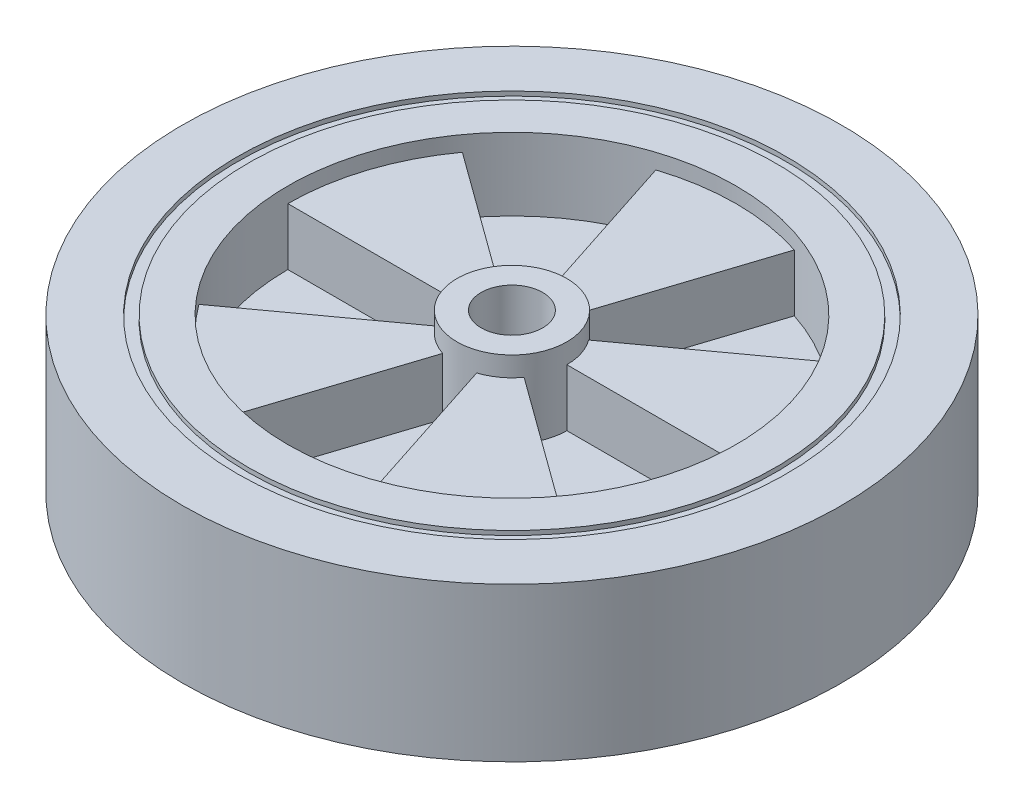
SolidWorks part; units mm, degrees
ref_plane "Front Plane" through (0, 0, 0) normal (0, 0, 1) x (1, 0, 0)
ref_plane "Top Plane" through (0, 0, 0) normal (0, 1, 0) x (1, 0, 0)
ref_plane "Right Plane" through (0, 0, 0) normal (1, 0, 0) x (0, 0, -1)
sketch "Sketch1" plane through (0, 0, 0) normal (0, 1, 0) x (1, 0, 0)
  circle A0 centre (0, 0) radius 7
  circle A1 centre (0, 0) radius 75
  circle A2 centre (0, 0) radius 51
  dimension "D1" = 14
  dimension "D2" = 150
  dimension "D3" = 102
extrude "Boss-Extrude1" add sketch "Sketch1" along normal mid plane 35 contours A1 A2
sketch "Sketch2" plane through (0, 0, 0) normal (0, 1, 0) x (1, 0, 0)
  circle A0 centre (0, 0) radius 12.5
  circle A1 centre (0, 0) radius 7
  dimension "D1" = 25
  dimension "D2" = 14
extrude "Boss-Extrude2" add sketch "Sketch2" along normal mid plane 37 separate body
sketch "Sketch3" plane through (0, 0, 0) normal (0, 1, 0) x (1, 0, 0)
  line L0 (0, 12.5) -> (0, 51) construction
  line L1 (3.8627, 11.8882) -> (15.7599, 48.5039)
  line L2 (-3.8627, 11.8882) -> (-15.7599, 48.5039)
  line L3 (12.5, 0) -> (51, 0)
  line L4 (10.1127, 7.3473) -> (41.2599, 29.977)
  line L5 (3.8627, -11.8882) -> (15.7599, -48.5039)
  line L6 (10.1127, -7.3473) -> (41.2599, -29.977)
  line L7 (-10.1127, -7.3473) -> (-41.2599, -29.977)
  line L8 (-3.8627, -11.8882) -> (-15.7599, -48.5039)
  line L9 (-12.5, 0) -> (12.5, 0) construction
  line L10 (0, 12.5) -> (0, -12.5) construction
  line L11 (-10.1127, 7.3473) -> (-41.2599, 29.977)
  line L12 (-12.5, 0) -> (-51, 0)
  circle A0 centre (0, 0) radius 12.5 construction
  circle A1 centre (0, 0) radius 12.5
  circle A2 centre (0, 0) radius 51 construction
  circle A3 centre (0, 0) radius 51
  point P27 (0, 0)
  point P35 (0, 0)
  dimension "D1" = 18
  dimension "D2" = 18
  dimension "D3" = 5
extrude "Boss-Extrude3" add sketch "Sketch3" along normal mid plane 28 contours L11 A3 L12 A1 | L1 A3 L2 A1 | L3 A3 L4 A1 | L5 A3 L6 A1 | L7 A3 L8 A1
sketch "Sketch5" plane through (0, 0, 0) normal (0, 1, 0) x (1, 0, 0)
  line L0 (3.8627, 11.8882) -> (15.7599, 48.5039) construction
  line L1 (10.1127, 7.3473) -> (41.2599, 29.977) construction
  line L2 (12.5, 0) -> (51, 0) construction
  line L3 (10.1127, -7.3473) -> (41.2599, -29.977) construction
  line L4 (3.8627, -11.8882) -> (15.7599, -48.5039) construction
  line L5 (-3.8627, -11.8882) -> (-15.7599, -48.5039) construction
  line L6 (-12.5, 0) -> (-51, 0) construction
  line L7 (-10.1127, -7.3473) -> (-41.2599, -29.977) construction
  line L8 (-10.1127, 7.3473) -> (-41.2599, 29.977) construction
  line L9 (-3.8627, 11.8882) -> (-15.7599, 48.5039) construction
  line L10 (3.8627, 11.8882) -> (15.7599, 48.5039)
  line L11 (10.1127, 7.3473) -> (41.2599, 29.977)
  line L12 (12.5, 0) -> (51, 0)
  line L13 (10.1127, -7.3473) -> (41.2599, -29.977)
  line L14 (3.8627, -11.8882) -> (15.7599, -48.5039)
  line L15 (-3.8627, -11.8882) -> (-15.7599, -48.5039)
  line L16 (-12.5, 0) -> (-51, 0)
  line L17 (-10.1127, -7.3473) -> (-41.2599, -29.977)
  line L18 (-10.1127, 7.3473) -> (-41.2599, 29.977)
  line L19 (-3.8627, 11.8882) -> (-15.7599, 48.5039)
  circle A0 centre (0, 0) radius 51 construction
  circle A1 centre (0, 0) radius 51
  circle A2 centre (0, 0) radius 12.5 construction
  circle A3 centre (0, 0) radius 12.5
sketch "Sketch6" plane through (0, 0, 0) normal (0, 1, 0) x (1, 0, 0)
  circle A0 centre (0, 0) radius 51 construction
  circle A1 centre (0, 0) radius 51
extrude "Boss-Extrude6" add sketch "Sketch6" along normal mid plane 2
sketch "Sketch7" plane through (0, 17.5, 0) normal (0, 1, 0) x (1, 0, 0)
  circle A0 centre (0, 0) radius 60
  circle A3 centre (0, 0) radius 62.5
  dimension "D1" = 120
  dimension "D2" = 125
extrude "Cut-Extrude1" cut sketch "Sketch7" against normal blind 1
mirror "Mirror2" about plane through (0, 0, 0) normal (0, 1, 0) of "Cut-Extrude1"
